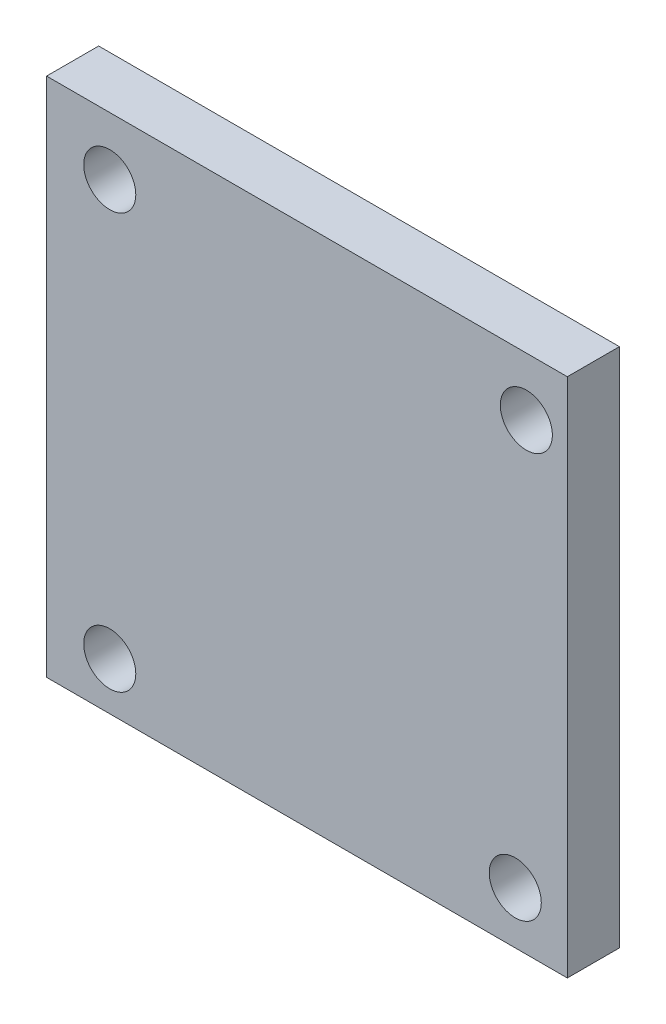
SolidWorks part; units mm, degrees
ref_plane "Front Plane" through (0, 0, 0) normal (0, 0, 1) x (1, 0, 0)
ref_plane "Top Plane" through (0, 0, 0) normal (0, 1, 0) x (1, 0, 0)
ref_plane "Right Plane" through (0, 0, 0) normal (1, 0, 0) x (0, 0, -1)
sketch "Sketch1" plane through (0, 0, 0) normal (0, 0, 1) x (1, 0, 0)
  line L0 (-41.9294, -21.8654) -> (8.0706, -21.8654)
  line L2 (-41.9294, 28.1346) -> (-41.9294, -21.8654)
  line L4 (8.0706, 28.1346) -> (8.0706, -21.8654)
  line L5 (-41.9294, 28.1346) -> (8.0706, 28.1346)
  circle A0 centre (-35.8653, 22.557) radius 2.5
  circle A1 centre (4.1347, 22.557) radius 2.5
  circle A2 centre (-35.8653, -17.2885) radius 2.5
  circle A3 centre (3.0706, -16.8654) radius 2.5
  dimension "D1" = 50
  dimension "D2" = 50
extrude "Boss-Extrude2" add sketch "Sketch1" along normal blind 5
